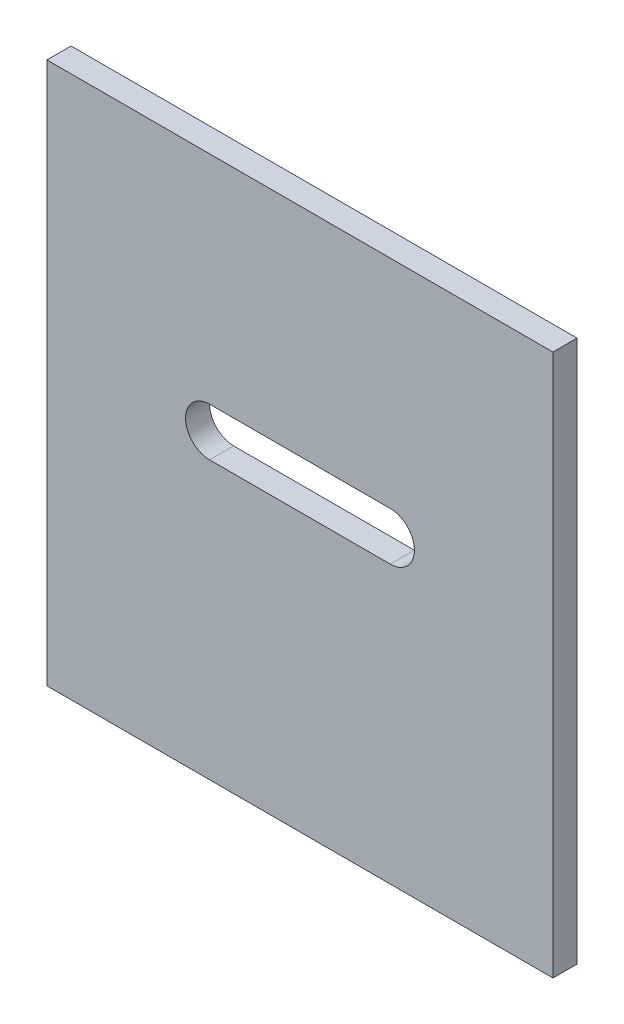
SolidWorks part; units mm, degrees
ref_plane "Front Plane" through (0, 0, 0) normal (0, 0, 1) x (1, 0, 0)
ref_plane "Top Plane" through (0, 0, 0) normal (0, 1, 0) x (1, 0, 0)
ref_plane "Right Plane" through (0, 0, 0) normal (1, 0, 0) x (0, 0, -1)
sketch "Sketch1" plane through (0, 0, 0) normal (0, 0, 1) x (1, 0, 0)
  line L1 (-21, 22.5) -> (21, 22.5)
  line L2 (-21, 22.5) -> (-21, -22.5)
  line L3 (-21, -22.5) -> (21, -22.5)
  line L4 (21, 22.5) -> (21, -22.5)
  line L5 (-21, 22.5) -> (21, -22.5) construction
  line L6 (-21, -22.5) -> (21, 22.5) construction
  point P0 (0, 0)
  dimension "D1" = 45
  dimension "D2" = 42
extrude "Boss-Extrude1" add sketch "Sketch1" along normal blind 2
sketch "Sketch2" plane through (0, 0, 2) normal (0, 0, 1) x (1, 0, 0)
  line L1 (-7.5, 2.5) -> (7.5, 2.5) construction
  line L2 (-7.5, 4.5) -> (7.5, 4.5)
  line L3 (-7.5, 0.5) -> (7.5, 0.5)
  line L4 (21, -22.5) -> (21, 22.5) construction
  line L5 (-21, -22.5) -> (21, -22.5) construction
  arc A0 (-7.5, 4.5) -> (-7.5, 0.5) centre (-7.5, 2.5) ccw
  arc A1 (7.5, 0.5) -> (7.5, 4.5) centre (7.5, 2.5) ccw
  point P0 (0, 2.5)
  dimension "D1" = 2
  dimension "D2" = 15
  dimension "D3" = 21
  dimension "D4" = 25
extrude "Cut-Extrude1" cut sketch "Sketch2" against normal blind 2
